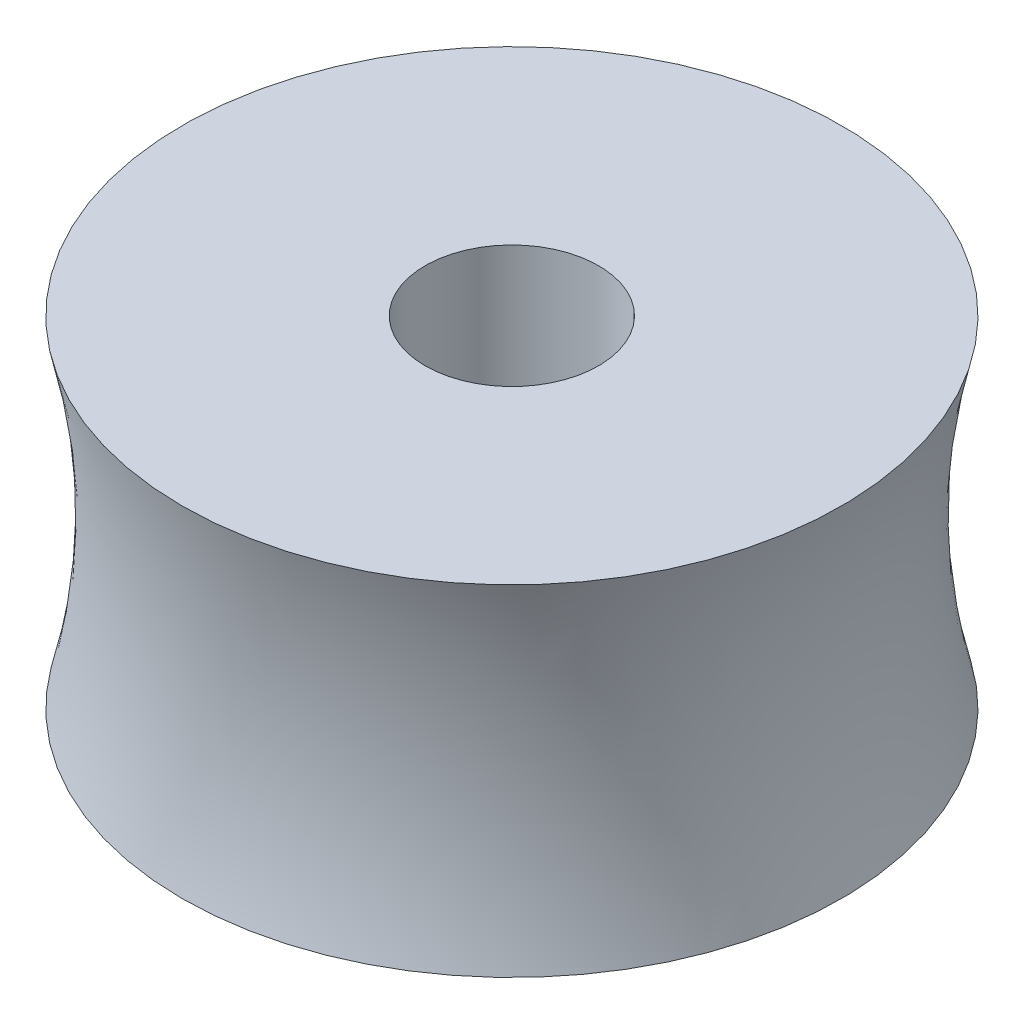
SolidWorks part; units mm, degrees
ref_plane "Front Plane" through (0, 0, 0) normal (0, 0, 1) x (1, 0, 0)
ref_plane "Top Plane" through (0, 0, 0) normal (0, 1, 0) x (1, 0, 0)
ref_plane "Right Plane" through (0, 0, 0) normal (1, 0, 0) x (0, 0, -1)
sketch "Sketch1" plane through (0, 0, 0) normal (1, 0, 0) x (0, 0, -1)
  line L0 (2.5, 0) -> (2.5, -9.8)
  line L1 (2.5, -9.8) -> (9.5, -9.8)
  line L3 (9.5, 0) -> (2.5, 0)
  line L4 (0, 0) -> (0, -54.1154) construction
  arc A0 (9.5, 0) -> (9.5, -9.8) centre (28.8905, -4.9) ccw
  dimension "D2" = 20
  dimension "D1" = 9.8
  dimension "D3" = 2.5
  dimension "D4" = 7
revolve "Revolve1" add sketch "Sketch1" angle 360 about L4
